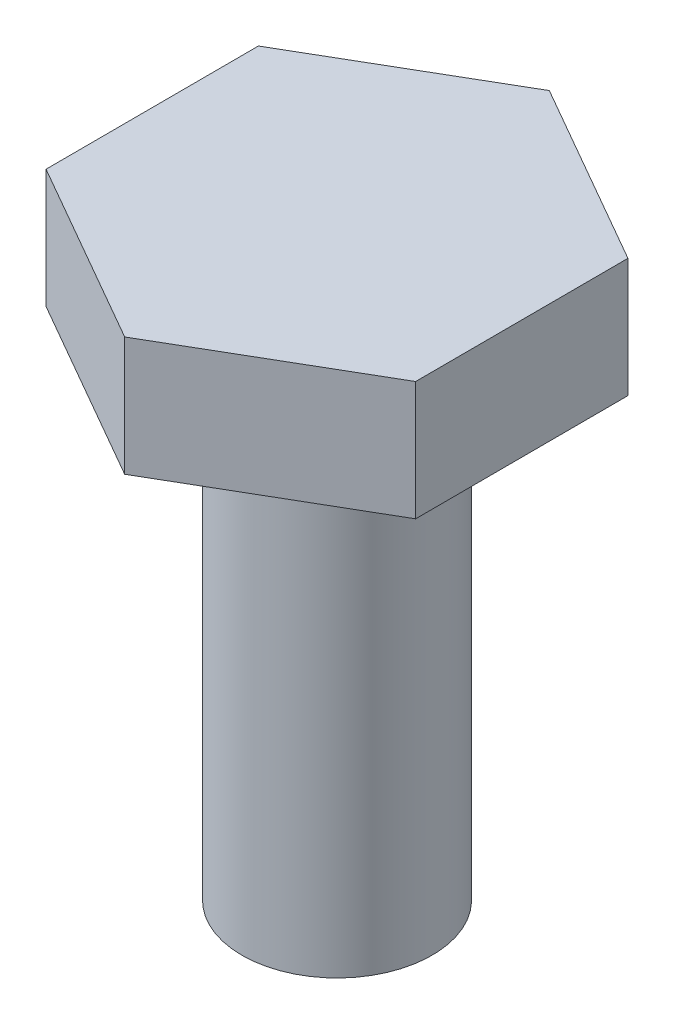
SolidWorks part; units mm, degrees
ref_plane "前视基准面" through (0, 0, 0) normal (0, 0, 1) x (1, 0, 0)
ref_plane "上视基准面" through (0, 0, 0) normal (0, 1, 0) x (1, 0, 0)
ref_plane "右视基准面" through (0, 0, 0) normal (1, 0, 0) x (0, 0, -1)
sketch "草图1" plane through (0, 0, 0) normal (0, 1, 0) x (1, 0, 0)
  circle A0 centre (0, 0) radius 0.8
  dimension "D1" = 1.6
extrude "凸台-拉伸1" add sketch "草图1" along normal blind 4
sketch "草图2" plane through (0, 4, 0) normal (0, 1, 0) x (1, 0, 0)
  line L1 (1.5522, -0.891) -> (1.5477, 0.8988)
  line L2 (1.5477, 0.8988) -> (-0.0045, 1.7898)
  line L3 (-0.0045, 1.7898) -> (-1.5522, 0.891)
  line L4 (-1.5522, 0.891) -> (-1.5477, -0.8988)
  line L5 (-1.5477, -0.8988) -> (0.0045, -1.7898)
  line L6 (0.0045, -1.7898) -> (1.5522, -0.891)
  circle A1 centre (0, 0) radius 1.55 construction
  dimension "D1" = 3.1
extrude "凸台-拉伸2" add sketch "草图2" along normal blind 1 contours L3 L4 L5 L6 L1 L2
